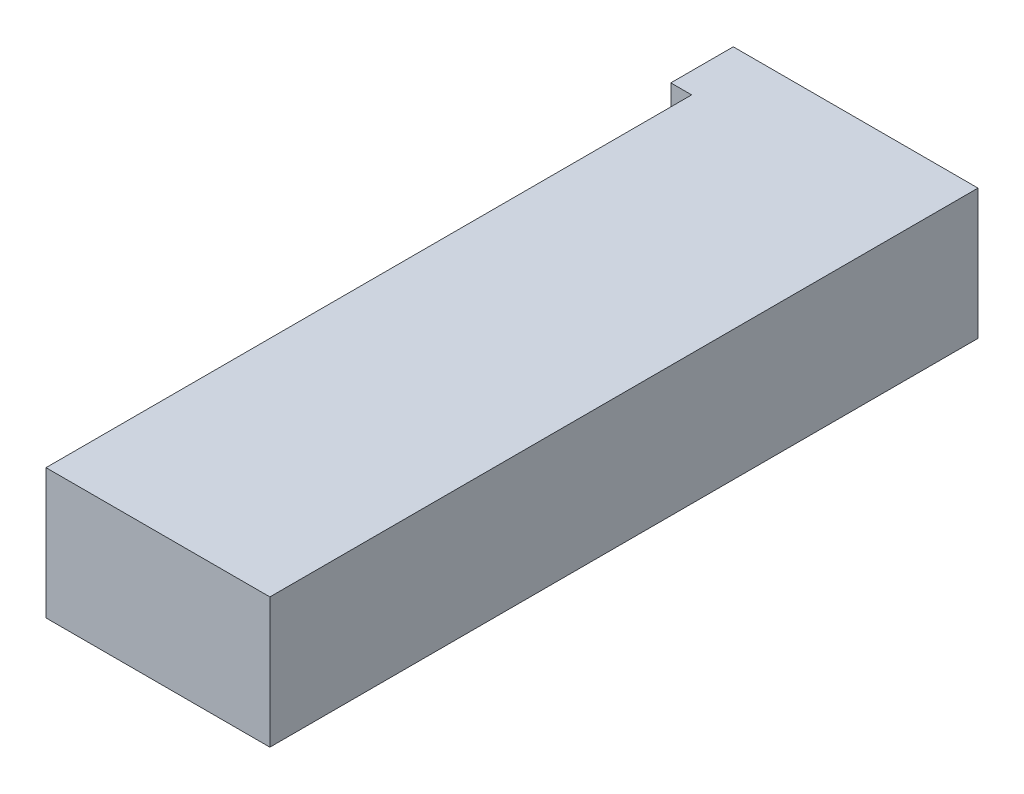
SolidWorks part; units mm, degrees
ref_plane "Alzado" through (0, 0, 0) normal (0, 0, 1) x (1, 0, 0)
ref_plane "Planta" through (0, 0, 0) normal (0, 1, 0) x (1, 0, 0)
ref_plane "Vista lateral" through (0, 0, 0) normal (1, 0, 0) x (0, 0, -1)
sketch "Croquis1" plane through (0, 0, 0) normal (0, 1, 0) x (1, 0, 0)
  line L1 (-21.5, 68) -> (21.5, 68)
  line L2 (-21.5, 68) -> (-21.5, -68)
  line L3 (-21.5, -68) -> (21.5, -68)
  line L4 (21.5, 68) -> (21.5, -68)
  line L5 (-21.5, 68) -> (21.5, -68) construction
  line L6 (-21.5, -68) -> (21.5, 68) construction
  line L7 (-25.5, 68) -> (21.5, 68)
  line L8 (-25.5, 68) -> (-25.5, 56)
  line L9 (-25.5, 56) -> (21.5, 56)
  line L10 (21.5, 68) -> (21.5, 56)
  point P0 (0, 0)
  point P10 (-25.5, 68)
  dimension "D1" = 43
  dimension "D2" = 136
  dimension "D3" = 47
  dimension "D4" = 4
  dimension "D5" = 12
extrude "Saliente-Extruir1" add sketch "Croquis1" along normal blind 25 contours L2 L9 L4 L1 | L9 L2 L3 L4 | L8 L9 L2 L7
